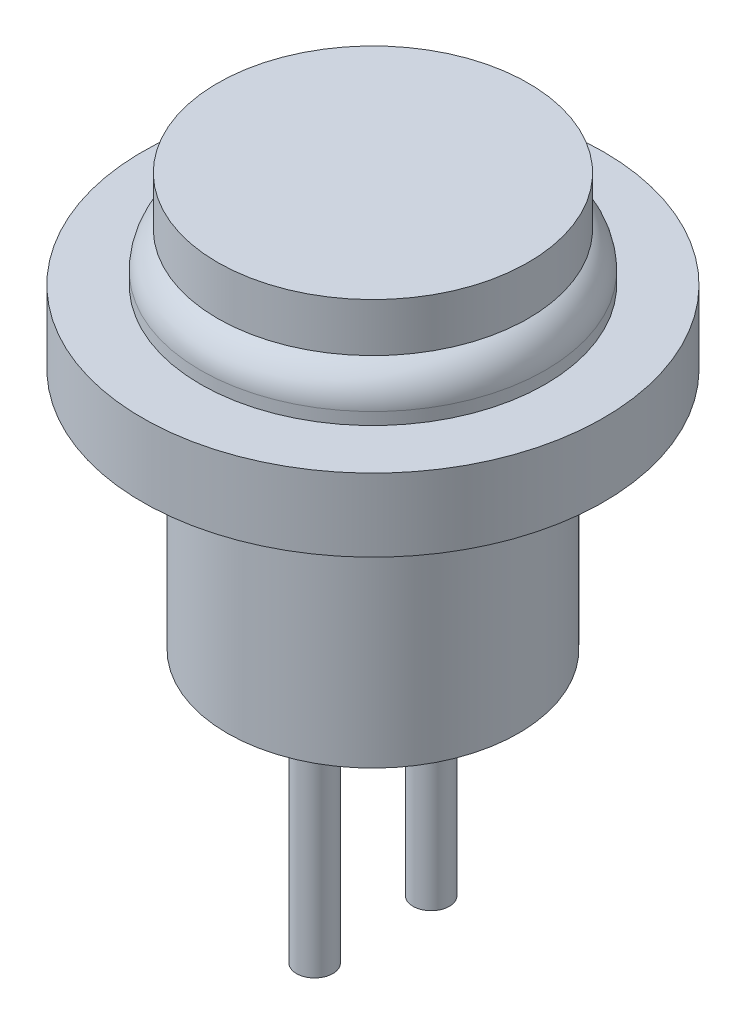
SolidWorks part; units mm, degrees
ref_plane "前视基准面" through (0, 0, 0) normal (0, 0, 1) x (1, 0, 0)
ref_plane "上视基准面" through (0, 0, 0) normal (0, 1, 0) x (1, 0, 0)
ref_plane "右视基准面" through (0, 0, 0) normal (1, 0, 0) x (0, 0, -1)
sketch "草图1" plane through (0, 0, 0) normal (0, 1, 0) x (1, 0, 0)
  circle A0 centre (0, 0) radius 7.1
  dimension "D1" = 14.2
extrude "拉伸1" add sketch "草图1" along normal blind 2
fillet "圆角1" radius 1.5 1 edges at (0, 2, 7.1)
sketch "草图2" plane through (0, 2, 0) normal (0, 1, 0) x (-1, 0, 0)
  circle A0 centre (0, 0) radius 6.4
  dimension "D1" = 12.8
extrude "拉伸2" add sketch "草图2" along normal blind 2
sketch "草图3" plane through (0, 0, 0) normal (0, -1, 0) x (1, 0, 0)
  circle A0 centre (0, 0) radius 6
  dimension "D1" = 12
extrude "拉伸3" add sketch "草图3" along normal blind 13
sketch "草图4" plane through (0, -13, 0) normal (0, -1, 0) x (1, 0, 0)
  line L0 (0, 5.4821) -> (0, -6.0169) construction
  circle A0 centre (0, -2.4) radius 0.75
  circle A1 centre (0, 2.4) radius 0.75
  dimension "D1" = 1.5
  dimension "D2" = 1.5
  dimension "D3" = 2.4
  dimension "D4" = 2.4
extrude "拉伸4" add sketch "草图4" along normal blind 10
sketch "草图5" plane through (0, 0, 0) normal (0, -1, 0) x (1, 0, 0)
  circle A0 centre (0, 0) radius 6
  circle A1 centre (0, 0) radius 6 construction
  circle A2 centre (0, 0) radius 9.5
  dimension "D1" = 19
extrude "拉伸5" add sketch "草图5" along normal blind 3
